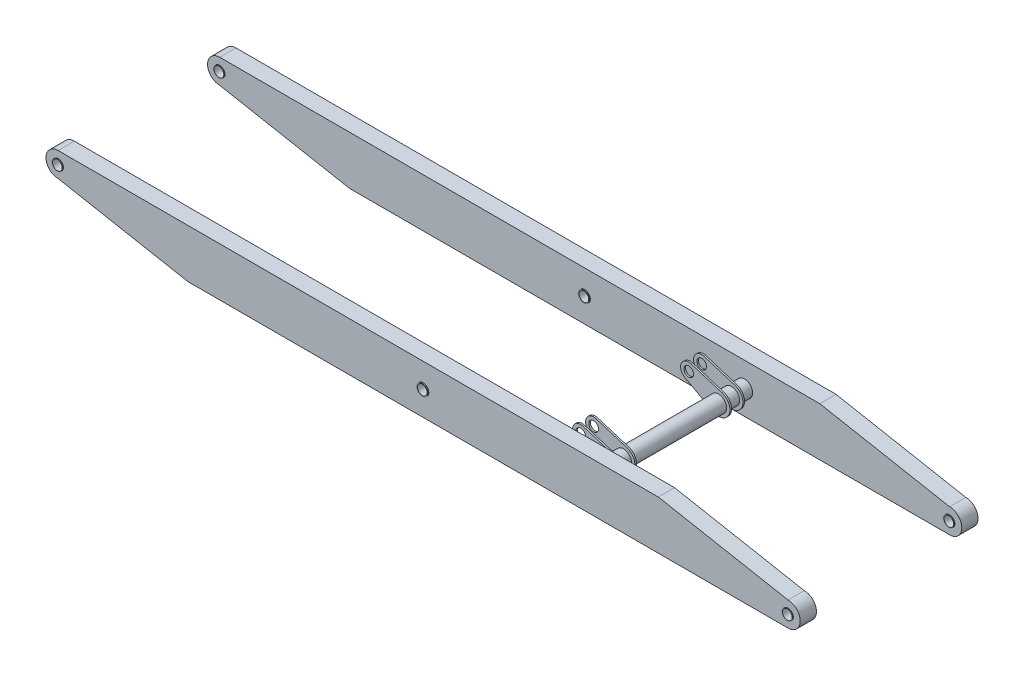
SolidWorks part; units mm, degrees
ref_plane "前视基准面" through (0, 0, 0) normal (0, 0, 1) x (1, 0, 0)
ref_plane "上视基准面" through (0, 0, 0) normal (0, 1, 0) x (1, 0, 0)
ref_plane "右视基准面" through (0, 0, 0) normal (1, 0, 0) x (0, 0, -1)
sketch "草图1" plane through (0, 0, 0) normal (0, 0, 1) x (1, 0, 0)
  line L0 (-60.1324, -127.5332) -> (739.8676, -277.5332)
  line L1 (-60.1324, 22.4668) -> (3639.8676, 22.4668)
  line L3 (739.8676, -277.5332) -> (4439.8676, -277.5332)
  line L5 (4439.8676, -127.5332) -> (3639.8676, 22.4668)
  arc A0 (-60.1324, 22.4668) -> (-60.1324, -127.5332) centre (-60.1324, -52.5332) ccw
  arc A1 (4439.8676, -277.5332) -> (4439.8676, -127.5332) centre (4439.8676, -202.5332) ccw
extrude "凸台-拉伸1" add sketch "草图1" along normal blind 100
sketch "草图2" plane through (0, 0, 100) normal (0, 0, 1) x (1, 0, 0)
  circle A0 centre (-60.1324, -52.5332) radius 30
  circle A1 centre (4439.8676, -202.5332) radius 30
extrude "切除-拉伸1" cut sketch "草图2" against normal blind 100
sketch "草图3" plane through (0, 0, 0) normal (0, 0, -1) x (-1, 0, 0)
  circle A0 centre (-4439.8676, -202.5332) radius 30
  circle A1 centre (-4439.8676, -202.5332) radius 32.5
  circle A2 centre (60.1324, -52.5332) radius 30
  circle A3 centre (60.1324, -52.5332) radius 32.5
extrude "凸台-拉伸2" add sketch "草图3" along normal blind 5
sketch "草图4" plane through (0, 0, 100) normal (0, 0, 1) x (1, 0, 0)
  circle A0 centre (-60.1324, -52.5332) radius 30 construction
  circle A1 centre (-60.1324, -52.5332) radius 32.5
  circle A2 centre (-60.1324, -52.5332) radius 32.5
  circle A3 centre (-60.1324, -52.5332) radius 30
  circle A4 centre (4439.8676, -202.5332) radius 32.5 construction
  circle A5 centre (4439.8676, -202.5332) radius 32.5
  circle A6 centre (4439.8676, -202.5332) radius 30 construction
  circle A7 centre (4439.8676, -202.5332) radius 30
  dimension "D1" = 0
extrude "凸台-拉伸3" add sketch "草图4" along normal blind 5
sketch "草图5" plane through (0, 0, 0) normal (0, 0, -1) x (-1, 0, 0)
  circle A2 centre (-2189.8676, -127.5332) radius 30
extrude "切除-拉伸3" cut sketch "草图5" against normal blind 552
sketch "草图6" plane through (0, 0, 100) normal (0, 0, 1) x (1, 0, 0)
  circle A0 centre (2189.8676, -127.5332) radius 35
  circle A1 centre (2189.8676, -127.5332) radius 30
extrude "凸台-拉伸4" add sketch "草图6" along normal blind 5
sketch "草图7" plane through (0, 0, 0) normal (0, 0, -1) x (-1, 0, 0)
  circle A0 centre (-2189.8676, -127.5332) radius 35 construction
  circle A1 centre (-2189.8676, -127.5332) radius 35
  circle A2 centre (-2189.8676, -127.5332) radius 30 construction
  circle A3 centre (-2189.8676, -127.5332) radius 30
extrude "凸台-拉伸5" add sketch "草图7" along normal blind 5
sketch "草图8" plane through (0, 0, 0) normal (0, 0, -1) x (-1, 0, 0)
  circle A0 centre (-3175.4225, -127.5332) radius 50
extrude "凸台-拉伸6" add sketch "草图8" along normal blind 448
mirror "镜向1" about plane through (3175.4225, -127.5332, -448) normal (0, 0, -1) of bodies 109
ref_plane "基准面1" through (0, 0, -448) normal (0, 0, -1) x (-1, 0, 0)
ref_plane "基准面2" through (0, 0, -736) normal (0, 0, -1) x (-1, 0, 0)
sketch "草图9" plane through (0, 0, -736) normal (0, 0, -1) x (-1, 0, 0)
  line L2 (-3006.1576, -1.6388) -> (-3196.193, -60.6858)
  line L3 (-2967.2804, -93.2279) -> (-3141.7649, -188.9105)
  arc A0 (-3196.193, -60.6858) -> (-3141.7649, -188.9105) centre (-3175.4225, -127.5332) ccw
  arc A1 (-2967.2804, -93.2279) -> (-3006.1576, -1.6388) centre (-2991.3215, -49.387) ccw
  dimension "D2" = 200
  dimension "D3" = 140
  dimension "D4" = 100
extrude "凸台-拉伸7" add sketch "草图9" along normal blind 10
sketch "草图10" plane through (0, 0, -746) normal (0, 0, -1) x (-1, 0, 0)
  circle A0 centre (-2991.3215, -49.387) radius 30
extrude "切除-拉伸4" cut sketch "草图10" against normal blind 10
pattern_linear "阵列(线性)1" count 2 spacing 80 along (0, 0, -1) of "凸台-拉伸7"
mirror "镜向2" about plane through (0, 0, -448) normal (0, 0, -1) of "阵列(线性)1", "凸台-拉伸7"
sketch "草图11" plane through (0, 0, -826) normal (0, 0, -1) x (-1, 0, 0)
  circle A0 centre (-2991.3215, -49.387) radius 30 construction
  circle A1 centre (-2991.3215, -49.387) radius 30
extrude "切除-拉伸5" cut sketch "草图11" against normal blind 800
scale "Scale1" scale about centroid uniform scaling yes scale factor 0.345
